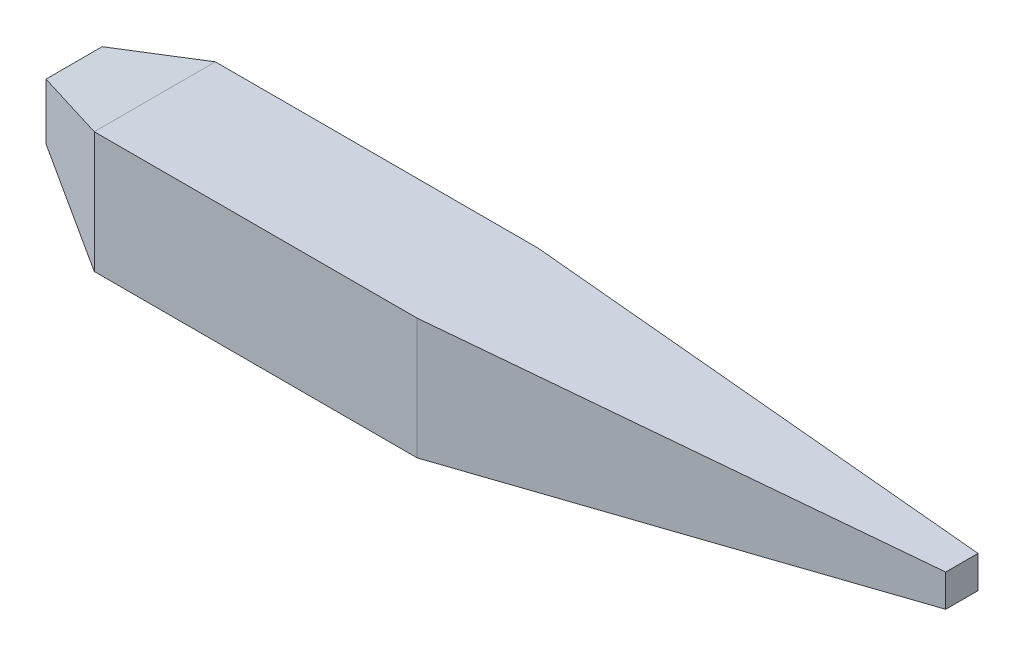
SolidWorks part; units mm, degrees
ref_plane "Front Plane" through (0, 0, 0) normal (0, 0, 1) x (1, 0, 0)
ref_plane "Top Plane" through (0, 0, 0) normal (0, 1, 0) x (1, 0, 0)
ref_plane "Right Plane" through (0, 0, 0) normal (1, 0, 0) x (0, 0, -1)
sketch "Sketch1" plane through (0, 0, 0) normal (0, 0, 1) x (1, 0, 0)
  line L1 (-200, -75) -> (200, -75)
  line L3 (-200, 75) -> (200, 75)
  line L5 (-200, -75) -> (200, 75) construction
  line L6 (-200, 75) -> (200, -75) construction
  line L12 (-200, 75) -> (-200, -75)
  line L13 (200, 75) -> (200, -75)
  point P0 (0, 0)
  dimension "D1" = 400
  dimension "D2" = 150
extrude "Boss-Extrude2" add sketch "Sketch1" along normal mid plane 150
ref_plane "Plane1" through (-300, 0, 0) normal (-1, 0, 0) x (0, 0, 1)
sketch "Sketch3" plane through (-300, 0, 0) normal (-1, 0, 0) x (0, 0, 1)
  line L5 (-34.7932, -8.2453) -> (34.7932, -8.2453)
  line L10 (-40, -40) -> (40, 40) construction
  line L11 (-40, 40) -> (40, -40) construction
  line L12 (-34.7932, -8.2453) -> (-34.7932, 61.3412)
  line L13 (-34.7932, 61.3412) -> (34.7932, 61.3412)
  line L14 (34.7932, -8.2453) -> (34.7932, 61.3412)
  point P4 (0, -8.2453)
  dimension "D1" = 80
  dimension "D2" = 80
sketch "Sketch4" plane through (0, 0, 0) normal (0, 0, 1) x (1, 0, 0)
  line L0 (-300, 0) -> (285.3862, 0) construction
  line L1 (-300, 40) -> (-300, -40) construction
loft "Loft1" add profiles "Sketch3" section face at (-200, 0, 0) section "Sketch3"
ref_plane "Plane2" through (800, 0, 0) normal (1, 0, 0) x (0, 0, -1)
sketch "Sketch5" plane through (800, 0, 0) normal (1, 0, 0) x (0, 0, -1)
  line L0 (-75, 75) -> (75, 75) construction
  line L1 (-20, 75) -> (20, 75)
  line L2 (-20, 75) -> (-20, 35)
  line L3 (-20, 35) -> (20, 35)
  line L4 (20, 75) -> (20, 35)
  point P6 (0, 75)
  dimension "D1" = 40
  dimension "D2" = 40
loft "Loft2" add profiles "Sketch5" section "Sketch5" section face at (200, 0, 0)
